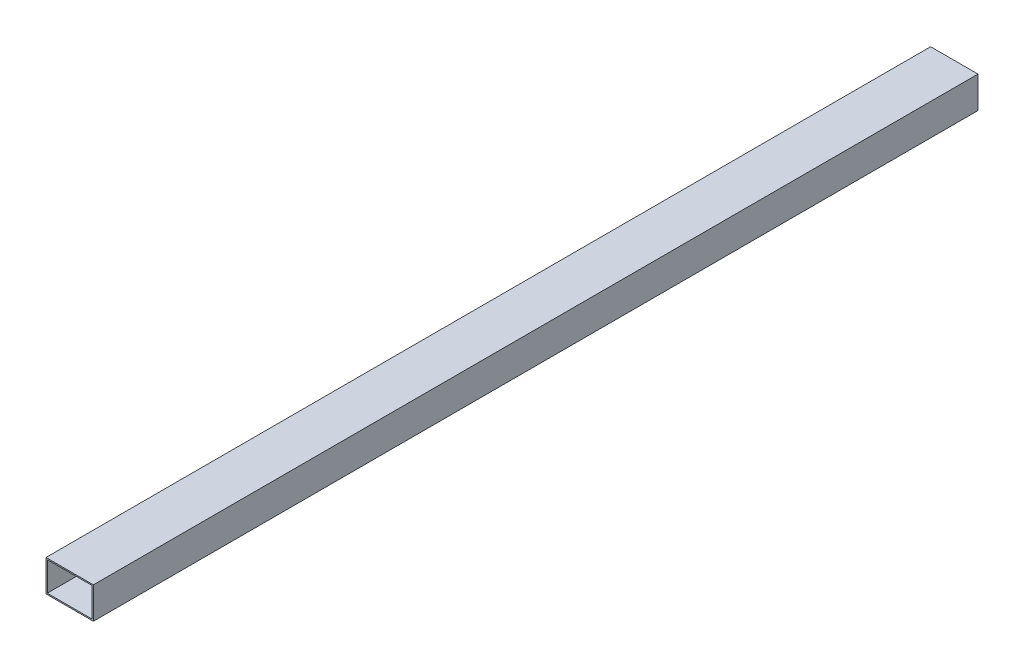
SolidWorks part; units mm, degrees
ref_plane "Alzado" through (0, 0, 0) normal (0, 0, 1) x (1, 0, 0)
ref_plane "Planta" through (0, 0, 0) normal (0, 1, 0) x (1, 0, 0)
ref_plane "Vista lateral" through (0, 0, 0) normal (1, 0, 0) x (0, 0, -1)
sketch "Croquis1" plane through (0, 0, 0) normal (0, 0, 1) x (1, 0, 0)
  line L1 (-107.863, 31.3707) -> (42.137, 31.3707)
  line L2 (-107.863, 31.3707) -> (-107.863, -68.6293)
  line L3 (-107.863, -68.6293) -> (42.137, -68.6293)
  line L4 (42.137, 31.3707) -> (42.137, -68.6293)
  line L5 (-103.863, 27.3707) -> (38.137, 27.3707)
  line L6 (-103.863, 27.3707) -> (-103.863, -64.6293)
  line L7 (-103.863, -64.6293) -> (38.137, -64.6293)
  line L8 (38.137, 27.3707) -> (38.137, -64.6293)
  dimension "D1" = 4
  dimension "D2" = 4
  dimension "D3" = 4
  dimension "D4" = 4
  dimension "D5" = 100
  dimension "D6" = 150
extrude "Saliente-Extruir2" add sketch "Croquis1" along normal blind 2800
